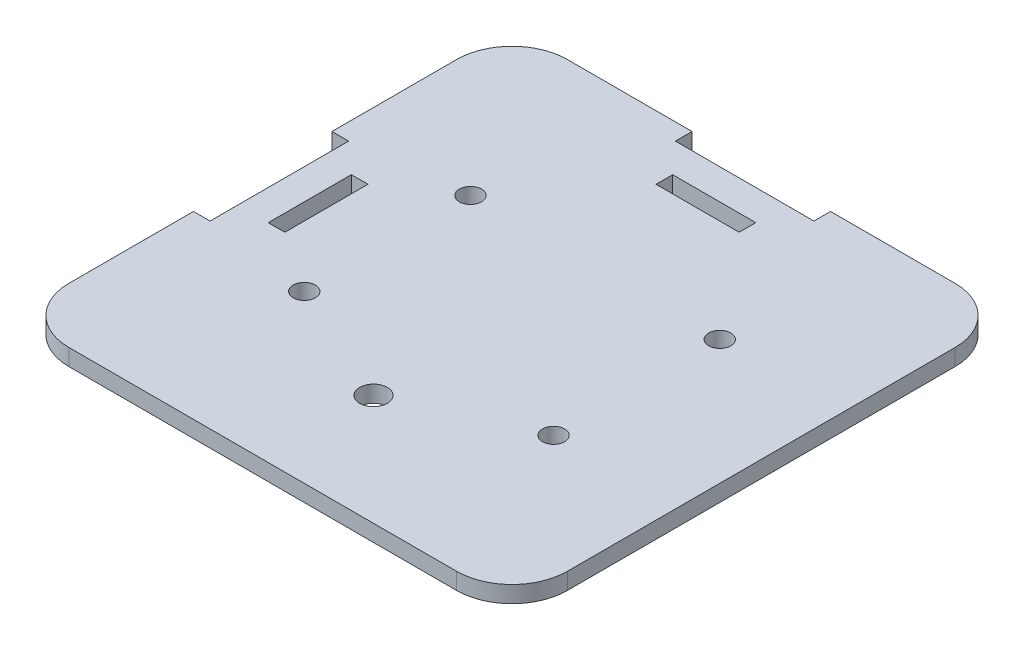
SolidWorks part; units mm, degrees
ref_plane "Front Plane" through (0, 0, 0) normal (0, 0, 1) x (1, 0, 0)
ref_plane "Top Plane" through (0, 0, 0) normal (0, 1, 0) x (1, 0, 0)
ref_plane "Right Plane" through (0, 0, 0) normal (1, 0, 0) x (0, 0, -1)
sketch "Sketch1" plane through (0, 0, 0) normal (0, 1, 0) x (1, 0, 0)
  line L1 (35, -45) -> (-35, -45)
  line L2 (45, -35) -> (45, 35)
  line L3 (35, 45) -> (-35, 45)
  line L4 (-45, -35) -> (-45, 35)
  line L5 (45, -45) -> (-45, 45) construction
  line L6 (45, 45) -> (-45, -45) construction
  line L7 (-45, 12.5) -> (-42, 12.5)
  line L8 (-45, 12.5) -> (-45, -12.5)
  line L9 (-45, -12.5) -> (-42, -12.5)
  line L10 (-42, 12.5) -> (-42, -12.5)
  line L11 (-12.5, 45) -> (12.5, 45)
  line L12 (-12.5, 45) -> (-12.5, 42)
  line L13 (-12.5, 42) -> (12.5, 42)
  line L14 (12.5, 45) -> (12.5, 42)
  arc A0 (-45, -35) -> (-35, -45) centre (-35, -35) ccw
  arc A1 (35, -45) -> (45, -35) centre (35, -35) ccw
  arc A2 (45, 35) -> (35, 45) centre (35, 35) ccw
  arc A3 (-45, 35) -> (-35, 45) centre (-35, 35) cw
  point P0 (0, 0)
  point P22 (-42, 0)
  point P23 (-45, 0)
  point P28 (0, 42)
  point P29 (0, 45)
  dimension "D1" = 10
  dimension "D2" = 3
  dimension "D3" = 25
  dimension "D4" = 0
  dimension "D5" = 3
  dimension "D6" = 25
  dimension "D7" = 0
  dimension "D8" = 90
  dimension "D9" = 90
extrude "Boss-Extrude1" add sketch "Sketch1" along normal blind 3 contours A3 L4 L7 L10 L9 A0 L1 A1 L2 A2 L3 L14 L13 L12
sketch "Sketch2" plane through (0, 3, 0) normal (0, 1, 0) x (1, 0, 0)
  line L0 (0, -1.65) -> (0, 1.65) construction
  line L1 (-1.65, 0) -> (1.65, 0) construction
  circle A0 centre (-22.5, 15) radius 2
  circle A1 centre (22.5, 15) radius 2
  circle A2 centre (22.5, -15) radius 2
  circle A3 centre (-22.5, -15) radius 2
  dimension "D1" = 22.5
  dimension "D2" = 15
extrude "Cut-Extrude1" cut sketch "Sketch2" against normal blind 3
sketch "Sketch3" plane through (0, 3, 0) normal (0, 1, 0) x (1, 0, 0)
  line L1 (7.5, 33.5) -> (-7.5, 33.5)
  line L2 (7.5, 33.5) -> (7.5, 36.5)
  line L3 (7.5, 36.5) -> (-7.5, 36.5)
  line L4 (-7.5, 33.5) -> (-7.5, 36.5)
  line L5 (7.5, 33.5) -> (-7.5, 36.5) construction
  line L6 (7.5, 36.5) -> (-7.5, 33.5) construction
  line L7 (-36.5, -7.5) -> (-33.5, -7.5)
  line L8 (-36.5, -7.5) -> (-36.5, 7.5)
  line L9 (-36.5, 7.5) -> (-33.5, 7.5)
  line L10 (-33.5, -7.5) -> (-33.5, 7.5)
  line L11 (-36.5, -7.5) -> (-33.5, 7.5) construction
  line L12 (-36.5, 7.5) -> (-33.5, -7.5) construction
  point P0 (0, 35)
  point P5 (-35, 0)
  dimension "D1" = 3
  dimension "D2" = 15
  dimension "D3" = 0
  dimension "D4" = 35
  dimension "D5" = 15
  dimension "D6" = 0
  dimension "D7" = 35
  dimension "D8" = 3
extrude "Cut-Extrude2" cut sketch "Sketch3" against normal blind 10
sketch "Sketch4" plane through (0, 3, 0) normal (0, 1, 0) x (1, 0, 0)
  circle A0 centre (0, -25) radius 2.5
  dimension "D1" = 25
extrude "Cut-Extrude3" cut sketch "Sketch4" against normal blind 14
